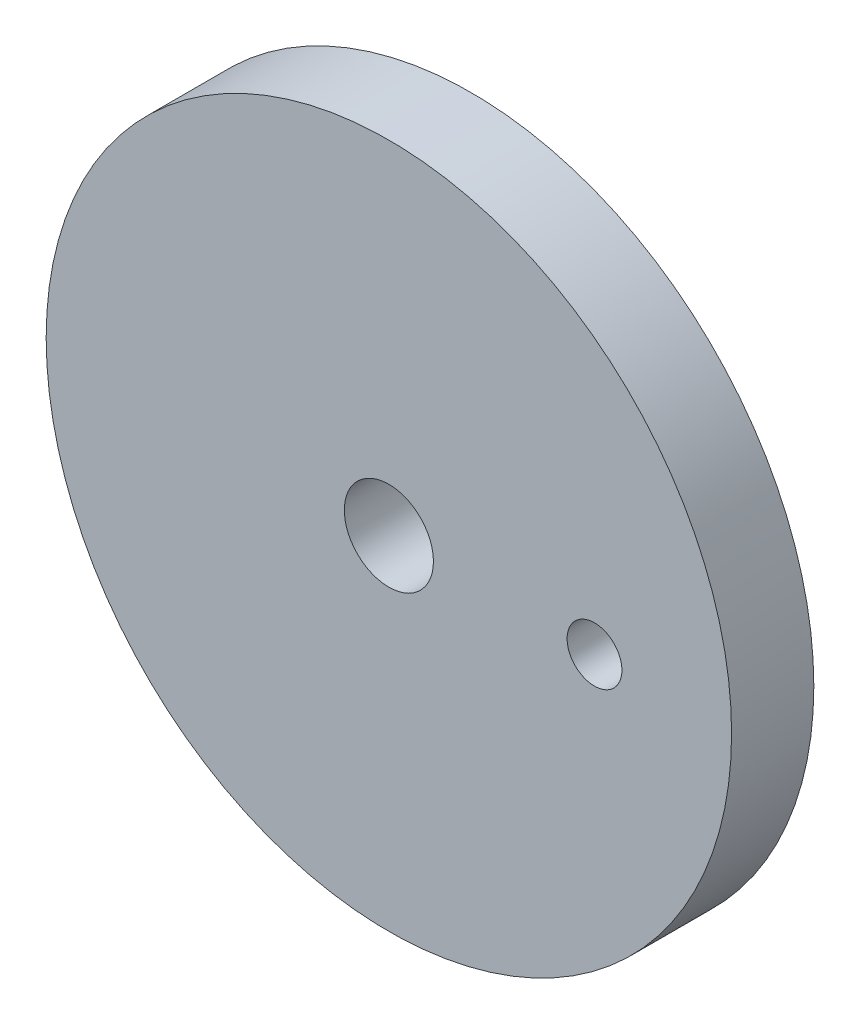
SolidWorks part; units mm, degrees
ref_plane "Plano frontal" through (0, 0, 0) normal (0, 0, 1) x (1, 0, 0)
ref_plane "Plano superior" through (0, 0, 0) normal (0, 1, 0) x (1, 0, 0)
ref_plane "Plano direito" through (0, 0, 0) normal (1, 0, 0) x (0, 0, -1)
sketch "Esboço1" plane through (0, 0, 0) normal (0, 0, 1) x (1, 0, 0)
  circle A0 centre (0, 0) radius 25
  circle A1 centre (0, 0) radius 3.25
  dimension "D1" = 50
  dimension "D2" = 6.5
extrude "Ressalto-extrusão1" add sketch "Esboço1" along normal mid plane 6
sketch "Esboço2" plane through (0, 0, 3) normal (0, 0, 1) x (1, 0, 0)
  circle A0 centre (15, 0) radius 2
  circle A1 centre (0, 0) radius 3.25 construction
  dimension "D1" = 4
  dimension "D2" = 15
extrude "Corte-extrusão1" cut sketch "Esboço2" against normal through all
